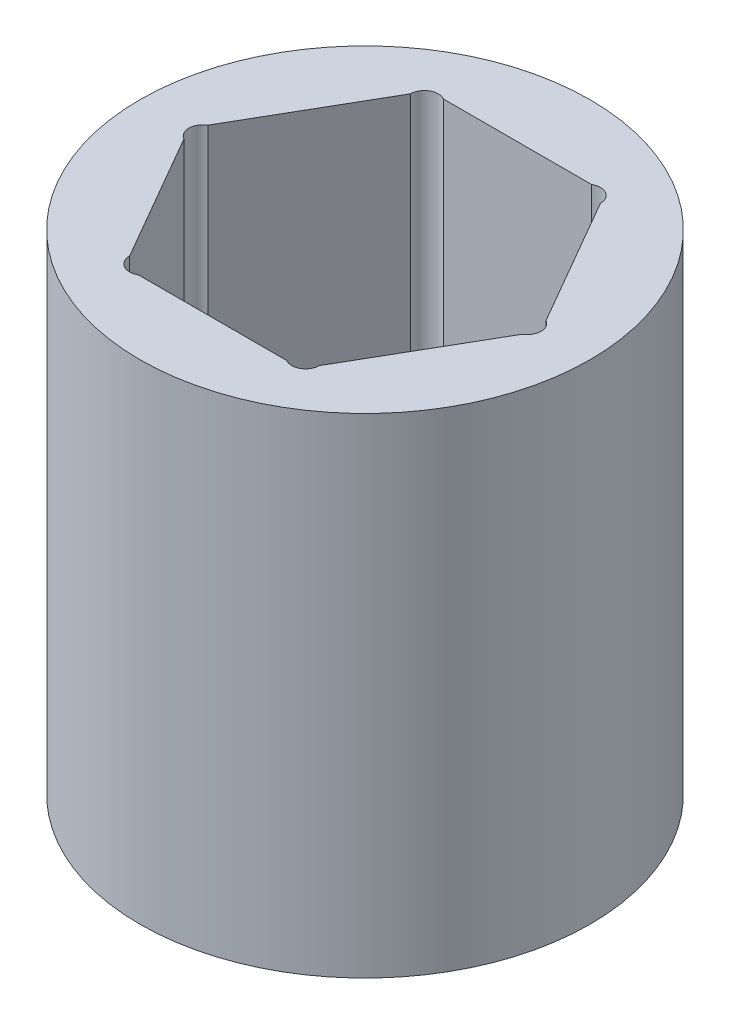
SolidWorks part; units mm, degrees
ref_plane "Front Plane" through (0, 0, 0) normal (0, 0, 1) x (1, 0, 0)
ref_plane "Top Plane" through (0, 0, 0) normal (0, 1, 0) x (1, 0, 0)
ref_plane "Right Plane" through (0, 0, 0) normal (1, 0, 0) x (0, 0, -1)
sketch "Sketch1" plane through (0, 0, 0) normal (0, 1, 0) x (1, 0, 0)
  line L0 (0, 0) -> (3.8128, 6.604) construction
  line L1 (7.6256, 0) -> (3.8128, 6.604)
  line L2 (3.8128, 6.604) -> (-3.8128, 6.604)
  line L3 (-3.8128, 6.604) -> (-7.6256, 0)
  line L4 (-7.6256, 0) -> (-3.8128, -6.604)
  line L5 (-3.8128, -6.604) -> (3.8128, -6.604)
  line L6 (3.8128, -6.604) -> (7.6256, 0)
  circle A0 centre (0, 0) radius 6.604 construction
  circle A1 centre (0, 0) radius 9.7536
  circle A2 centre (3.5128, 6.0844) radius 0.6
  circle A3 centre (7.0256, 0) radius 0.6
  circle A4 centre (3.5128, -6.0844) radius 0.6
  circle A5 centre (-3.5128, -6.0844) radius 0.6
  circle A6 centre (-7.0256, 0) radius 0.6
  circle A7 centre (-3.5128, 6.0844) radius 0.6
  point P12 (6.1191, 0.7461)
  point P13 (0, 0)
  point P25 (0, 0)
  dimension "D1" = 13.208
  dimension "D2" = 19.5072
  dimension "D3" = 1.2
  dimension "D4" = 6
extrude "Boss-Extrude1" add sketch "Sketch1" along normal blind 21.1836 contours A1 A7 L2 A2 L1 A3 L6 A4 L5 A5 L4 A6 L3
